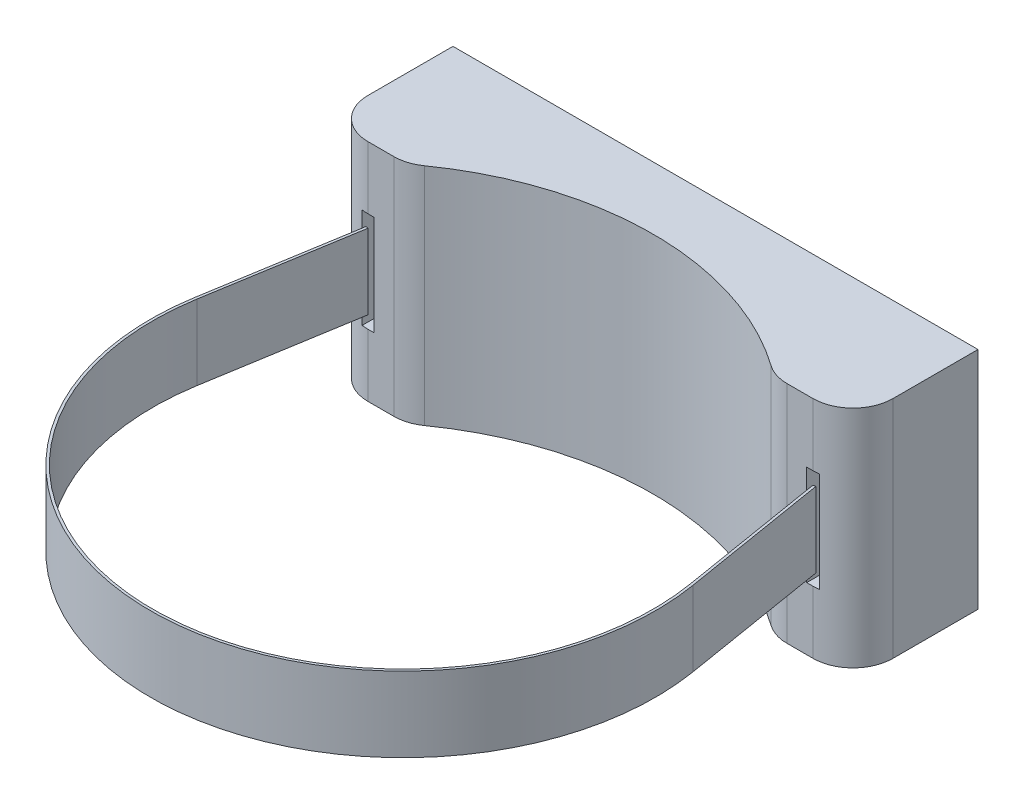
SolidWorks part; units mm, degrees
material "PPE"
ref_plane "Front" through (0, 0, 0) normal (0, 0, 1) x (1, 0, 0)
ref_plane "Top" through (0, 0, 0) normal (0, 1, 0) x (1, 0, 0)
ref_plane "Right" through (0, 0, 0) normal (1, 0, 0) x (0, 0, -1)
sketch "Sketch1" plane through (0, 0, 0) normal (0, 1, 0) x (1, 0, 0)
  line L0 (0, 0) -> (0, -152.4) construction
  line L1 (-133.35, 31.75) -> (133.35, 31.75)
  line L2 (-133.35, 31.75) -> (-133.35, -31.75)
  line L3 (-133.35, -31.75) -> (-93.1093, -31.75)
  line L4 (133.35, 31.75) -> (133.35, -31.75)
  line L5 (-133.35, 31.75) -> (133.35, -31.75) construction
  line L6 (-133.35, -31.75) -> (133.35, 31.75) construction
  line L7 (93.1093, -31.75) -> (133.35, -31.75)
  arc A0 (93.1093, -31.75) -> (-93.1093, -31.75) centre (0, -152.4) ccw
  point P0 (0, 0)
  dimension "D3" = 304.8
  dimension "D1" = 266.7
  dimension "D2" = 63.5
  dimension "D4" = 152.4
extrude "Boss-Extrude1" add sketch "Sketch1" along normal blind 114.3
fillet "Fillet1" radius 20.32 2 edges at (133.35, 57.15, 31.75) (-133.35, 57.15, 31.75)
fillet "Fillet2" radius 20.32 2 edges at (93.1093, 57.15, 31.75) (-93.1093, 57.15, 31.75)
sketch "Sketch2" plane through (0, 0, 31.75) normal (0, 0, 1) x (1, 0, 0)
  line L0 (-113.03, 114.3) -> (-113.03, 0) construction
  line L1 (-116.205, 82.55) -> (-109.855, 82.55)
  line L2 (-116.205, 82.55) -> (-116.205, 31.75)
  line L3 (-116.205, 31.75) -> (-109.855, 31.75)
  line L4 (-109.855, 82.55) -> (-109.855, 31.75)
  line L5 (-116.205, 82.55) -> (-109.855, 31.75) construction
  line L6 (-116.205, 31.75) -> (-109.855, 82.55) construction
  line L7 (113.03, 0) -> (113.03, 114.3) construction
  line L8 (109.855, 82.55) -> (116.205, 82.55)
  line L9 (109.855, 82.55) -> (109.855, 31.75)
  line L10 (109.855, 31.75) -> (116.205, 31.75)
  line L11 (116.205, 82.55) -> (116.205, 31.75)
  line L12 (109.855, 82.55) -> (116.205, 31.75) construction
  line L13 (109.855, 31.75) -> (116.205, 82.55) construction
  point P0 (-113.03, 57.15)
  point P7 (113.03, 57.15)
  dimension "D1" = 50.8
  dimension "D2" = 6.35
extrude "Cut-Extrude1" cut sketch "Sketch2" against normal through all
sketch "Sketch3" plane through (0, 31.75, 0) normal (0, 1, 0) x (1, 0, 0)
  line L0 (0, 0) -> (0, -127) construction
  line L1 (-113.03, -31.75) -> (-125.3136, -106.3721)
  line L2 (113.03, -31.75) -> (125.3136, -106.3721)
  arc A0 (-125.3136, -106.3721) -> (125.3136, -106.3721) centre (0, -127) ccw
  dimension "D1" = 254
  dimension "D2" = 127
extrude "Extrude-Thin1" add sketch "Sketch3" along normal blind 38.1 from offset 6.35 separate body thin
